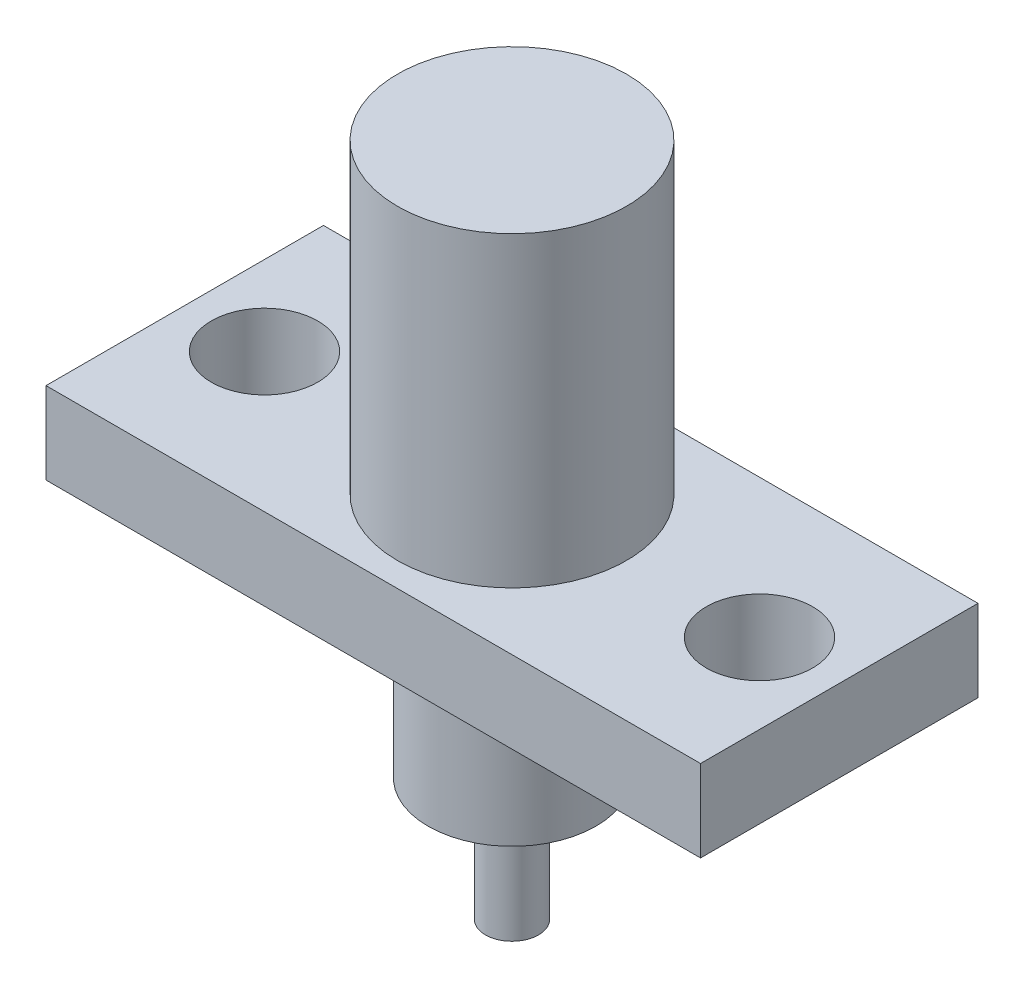
SolidWorks part; units mm, degrees
ref_plane "前视基准面" through (0, 0, 0) normal (0, 0, 1) x (1, 0, 0)
ref_plane "上视基准面" through (0, 0, 0) normal (0, 1, 0) x (1, 0, 0)
ref_plane "右视基准面" through (0, 0, 0) normal (1, 0, 0) x (0, 0, -1)
sketch "草图1" plane through (0, 0, 0) normal (0, 1, 0) x (1, 0, 0)
  line L0 (-6.05, 0) -> (6.05, 0)
  line L1 (-8, -3.3913) -> (8, -3.3913)
  line L2 (-8, -3.3913) -> (-8, 3.3913)
  line L3 (-8, 3.3913) -> (8, 3.3913)
  line L4 (8, -3.3913) -> (8, 3.3913)
  line L5 (-8, -3.3913) -> (8, 3.3913) construction
  line L6 (-8, 3.3913) -> (8, -3.3913) construction
  circle A0 centre (-6.05, 0) radius 1.3
  circle A1 centre (6.05, 0) radius 1.3
  point P0 (0, 0)
  point P10 (0, 0)
  dimension "D3" = 2.6
  dimension "D4" = 2.6
  dimension "D1" = 16
  dimension "D2" = 12.1
extrude "凸台-拉伸1" add sketch "草图1" along normal blind 2
sketch "草图2" plane through (0, 2, 0) normal (0, 1, 0) x (1, 0, 0)
  circle A0 centre (0, 0) radius 2.8
extrude "凸台-拉伸2" add sketch "草图2" along normal blind 7.5
sketch "草图3" plane through (0, 0, 0) normal (0, -1, 0) x (1, 0, 0)
  circle A0 centre (0, 0) radius 2.05
  dimension "D1" = 4.1
extrude "凸台-拉伸3" add sketch "草图3" along normal blind 4
sketch "草图4" plane through (0, -4, 0) normal (0, -1, 0) x (1, 0, 0)
  circle A0 centre (0, 0) radius 0.65
  dimension "D1" = 1.3
extrude "凸台-拉伸4" add sketch "草图4" along normal blind 3
